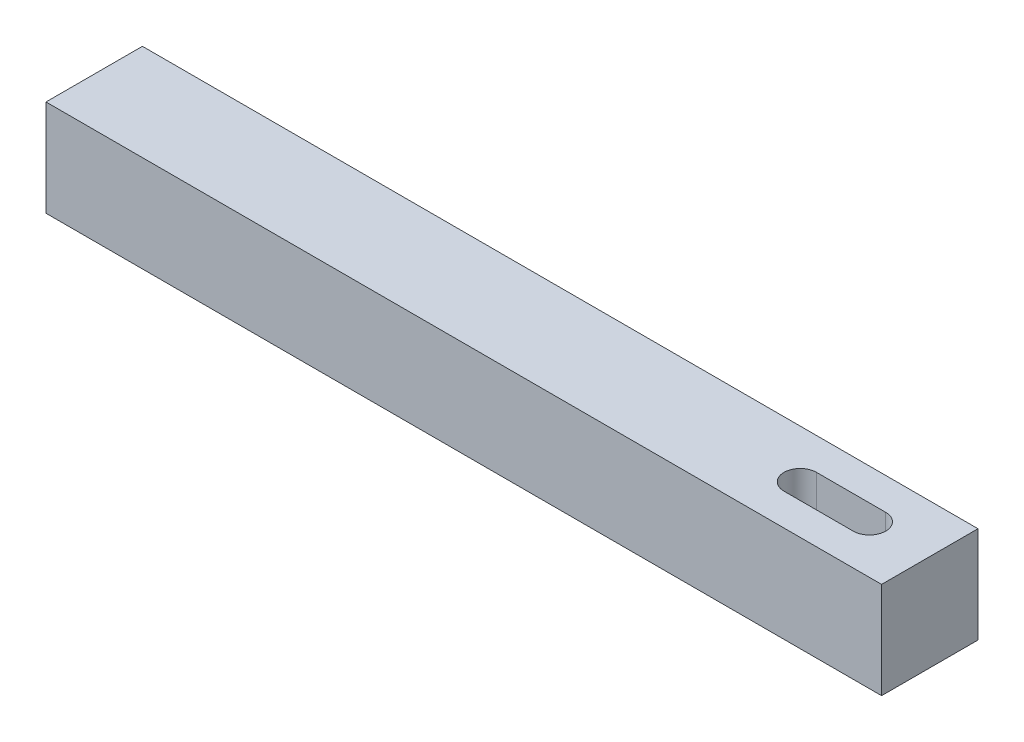
SolidWorks part; units mm, degrees
material "Fundición gris (SN)"
ref_plane "Alzado" through (0, 0, 0) normal (0, 0, 1) x (1, 0, 0)
ref_plane "Planta" through (0, 0, 0) normal (0, 1, 0) x (1, 0, 0)
ref_plane "Vista lateral" through (0, 0, 0) normal (1, 0, 0) x (0, 0, -1)
sketch "Croquis1" plane through (0, 0, 0) normal (1, 0, 0) x (0, 0, -1)
  line L1 (7.5, -7.5) -> (-7.5, -7.5)
  line L2 (7.5, -7.5) -> (7.5, 7.5)
  line L3 (7.5, 7.5) -> (-7.5, 7.5)
  line L4 (-7.5, -7.5) -> (-7.5, 7.5)
  line L5 (7.5, -7.5) -> (-7.5, 7.5) construction
  line L6 (7.5, 7.5) -> (-7.5, -7.5) construction
  point P0 (0, 0)
  dimension "D1" = 15
  dimension "D2" = 15
extrude "Saliente-Extruir1" add sketch "Croquis1" along normal mid plane 130
sketch "Croquis2" plane through (0, -7.5, 0) normal (0, -1, 0) x (1, 0, 0)
  line L0 (44.8471, 0) -> (55.614, 0) construction
  line L1 (44.8471, 2.5318) -> (55.614, 2.5318)
  line L2 (44.8471, -2.5318) -> (55.614, -2.5318)
  arc A0 (44.8471, 2.5318) -> (44.8471, -2.5318) centre (44.8471, 0) ccw
  arc A1 (55.614, -2.5318) -> (55.614, 2.5318) centre (55.614, 0) ccw
  point P2 (50.2306, 0)
  point P8 (44.8471, 0)
extrude "Cortar-Extruir1" cut sketch "Croquis2" against normal through all
